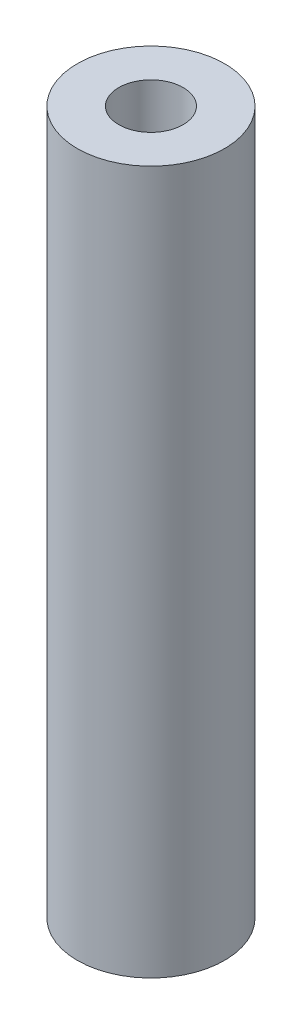
SolidWorks part; units mm, degrees
ref_plane "前视基准面" through (0, 0, 0) normal (0, 0, 1) x (1, 0, 0)
ref_plane "上视基准面" through (0, 0, 0) normal (0, 1, 0) x (1, 0, 0)
ref_plane "右视基准面" through (0, 0, 0) normal (1, 0, 0) x (0, 0, -1)
other "Configuration Table"
sketch "草图1" plane through (0, 0, 0) normal (0, 1, 0) x (1, 0, 0)
  circle A0 centre (0, 0) radius 1.75
  circle A1 centre (0, 0) radius 4
  dimension "D1" = 8
  dimension "D2" = 3.5
extrude "凸台-拉伸1" add sketch "草图1" along normal blind 38.2
